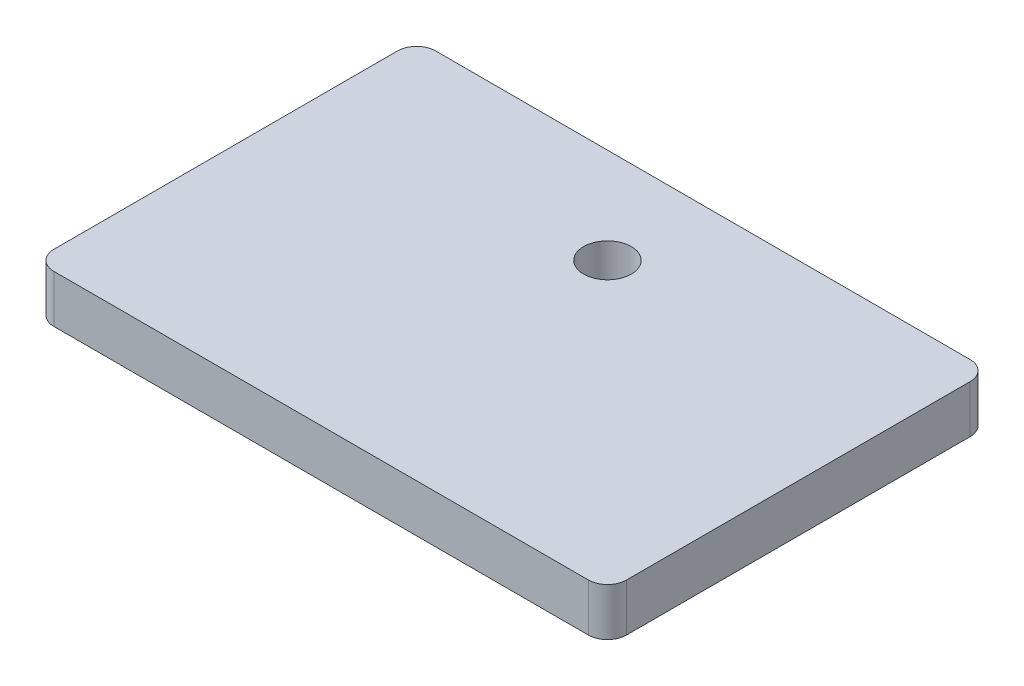
SolidWorks part; units mm, degrees
ref_plane "Front Plane" through (0, 0, 0) normal (0, 0, 1) x (1, 0, 0)
ref_plane "Top Plane" through (0, 0, 0) normal (0, 1, 0) x (1, 0, 0)
ref_plane "Right Plane" through (0, 0, 0) normal (1, 0, 0) x (0, 0, -1)
sketch "Sketch1" plane through (0, 0, 0) normal (0, 1, 0) x (1, 0, 0)
  line L1 (-38.1, -25.4) -> (38.1, -25.4)
  line L2 (-38.1, -25.4) -> (-38.1, 25.4)
  line L3 (-38.1, 25.4) -> (38.1, 25.4)
  line L4 (38.1, -25.4) -> (38.1, 25.4)
  line L5 (-38.1, -25.4) -> (38.1, 25.4) construction
  line L6 (-38.1, 25.4) -> (38.1, -25.4) construction
  point P0 (0, 0)
  dimension "D1" = 76.2
  dimension "D2" = 50.8
extrude "Boss-Extrude1" add sketch "Sketch1" along normal blind 6.35
fillet "Fillet1" radius 2.54 4 edges at (-38.1, 3.175, -25.4) (38.1, 3.175, -25.4) (38.1, 3.175, 25.4) (-38.1, 3.175, 25.4)
sketch "Sketch2" plane through (0, 6.35, 0) normal (0, 1, 0) x (1, 0, 0)
  line L0 (-35.56, -25.4) -> (35.56, -25.4) construction
  circle A0 centre (0, 12.7) radius 3.175
  point P5 (0, 0)
  dimension "D2" = 6.35
  dimension "D1" = 38.1
extrude "Cut-Extrude1" cut sketch "Sketch2" against normal blind 6.35
